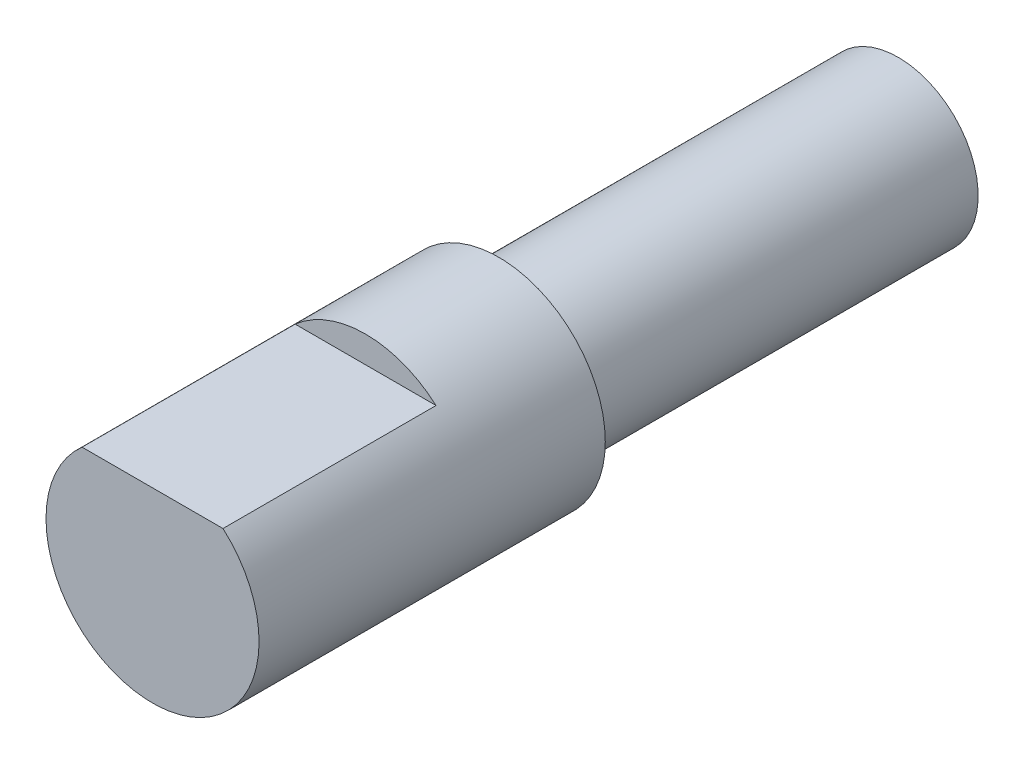
SolidWorks part; units mm, degrees
material "1060 합금"
ref_plane "정면" through (0, 0, 0) normal (0, 0, 1) x (1, 0, 0)
ref_plane "윗면" through (0, 0, 0) normal (0, 1, 0) x (1, 0, 0)
ref_plane "우측면" through (0, 0, 0) normal (1, 0, 0) x (0, 0, -1)
sketch "스케치1" plane through (0, 0, 0) normal (0, 0, 1) x (1, 0, 0)
  circle A0 centre (0, 0) radius 4
extrude "보스-돌출1" add sketch "스케치1" along normal blind 28
sketch "스케치2" plane through (0, 0, 0) normal (0, 0, -1) x (-1, 0, 0)
  line L0 (0, 0) -> (0, 6.3785) construction
  line L2 (-5.339, 4.9372) -> (5.9296, 4.9372)
  line L3 (-5.339, 4.9372) -> (-5.339, 3)
  line L4 (-5.339, 3) -> (5.9296, 3)
  line L5 (5.9296, 4.9372) -> (5.9296, 3)
  dimension "D1" = 3
extrude "컷-돌출1" cut sketch "스케치2" against normal blind 15
sketch "스케치3" plane through (0, 0, 28) normal (0, 0, 1) x (1, 0, 0)
  line L1 (-4.1373, 5.4333) -> (4.6272, 5.4333)
  line L2 (-4.1373, 5.4333) -> (-4.1373, 3)
  line L3 (-4.1373, 3) -> (4.6272, 3)
  line L4 (4.6272, 5.4333) -> (4.6272, 3)
  dimension "D1" = 3
extrude "컷-돌출2" cut sketch "스케치3" against normal blind 8
sketch "스케치4" plane through (0, 0, 0) normal (0, 0, -1) x (-1, 0, 0)
  circle A0 centre (0, 0) radius 4.0027
extrude "컷-돌출3" cut sketch "스케치4" against normal blind 15
sketch "스케치5" plane through (0, 0, 15) normal (0, 0, -1) x (-1, 0, 0)
  circle A0 centre (0, 0) radius 3
extrude "보스-돌출2" add sketch "스케치5" along normal blind 15
